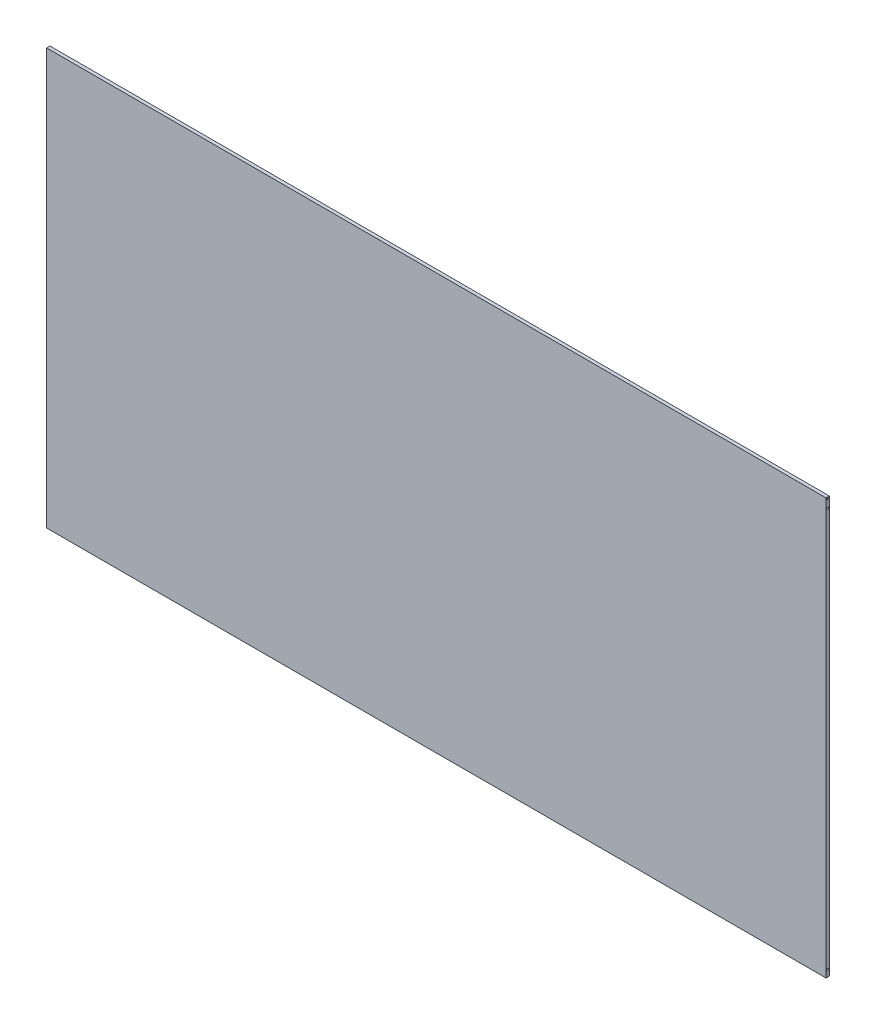
SolidWorks part; units mm, degrees
ref_plane "Front Plane" through (0, 0, 0) normal (0, 0, 1) x (1, 0, 0)
ref_plane "Top Plane" through (0, 0, 0) normal (0, 1, 0) x (1, 0, 0)
ref_plane "Right Plane" through (0, 0, 0) normal (1, 0, 0) x (0, 0, -1)
sketch "Sketch1" plane through (0, 0, 0) normal (0, 0, 1) x (1, 0, 0)
  line L1 (-595, 317.5) -> (595, 317.5)
  line L2 (-595, 317.5) -> (-595, -317.5)
  line L3 (-595, -317.5) -> (595, -317.5)
  line L4 (595, 317.5) -> (595, -317.5)
  line L5 (-595, 317.5) -> (595, -317.5) construction
  line L6 (-595, -317.5) -> (595, 317.5) construction
  point P0 (0, 0)
  dimension "D1" = 635
  dimension "D2" = 1190
extrude "Boss-Extrude1" add sketch "Sketch1" along normal blind 5
sketch "Sketch2" plane through (-595, 0, 0) normal (-1, 0, 0) x (0, 0, 1)
  circle A0 centre (2.5, -320) radius 1.2
  circle A1 centre (2.5, 302.5) radius 1.5
  dimension "D1" = 2.4
  dimension "D2" = 3
extrude "Cut-Extrude1" cut sketch "Sketch2" against normal blind 10
sketch "Sketch4" plane through (595, 0, 0) normal (1, 0, 0) x (0, 0, -1)
  circle A0 centre (-2.5, 302.5) radius 1.5
  circle A1 centre (-2.5, -307.5) radius 1.5
  dimension "D1" = 3
  dimension "D2" = 3
extrude "Cut-Extrude2" cut sketch "Sketch4" against normal blind 10
sketch "Sketch5" plane through (595, 0, 0) normal (1, 0, 0) x (0, 0, -1)
  circle A0 centre (-2.5, 315) radius 1.2
  dimension "D1" = 2.4
extrude "Cut-Extrude3" cut sketch "Sketch5" against normal blind 10
